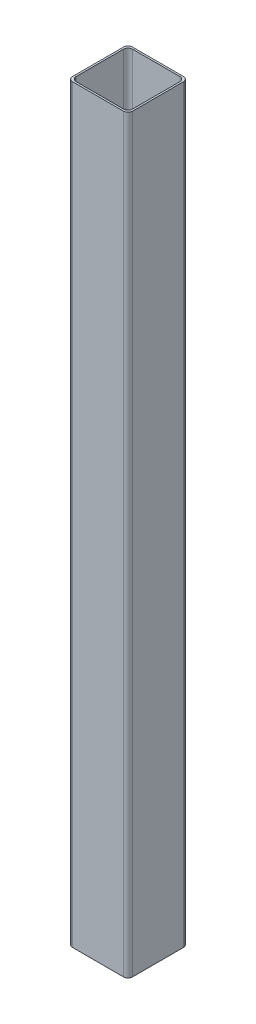
SolidWorks part; units mm, degrees
ref_plane "Plano frontal" through (0, 0, 0) normal (0, 0, 1) x (1, 0, 0)
ref_plane "Plano superior" through (0, 0, 0) normal (0, 1, 0) x (1, 0, 0)
ref_plane "Plano direito" through (0, 0, 0) normal (1, 0, 0) x (0, 0, -1)
sketch "Esboço1" plane through (0, 0, 0) normal (0, 1, 0) x (1, 0, 0)
  line L0 (-18.8, -18.8) -> (-18.8, 18.8)
  line L1 (20, -20) -> (-20, -20)
  line L2 (20, -20) -> (20, 20)
  line L3 (20, 20) -> (-20, 20)
  line L4 (-20, -20) -> (-20, 20)
  line L5 (20, -20) -> (-20, 20) construction
  line L6 (20, 20) -> (-20, -20) construction
  line L7 (18.8, 18.8) -> (-18.8, 18.8)
  line L8 (18.8, -18.8) -> (18.8, 18.8)
  line L9 (18.8, -18.8) -> (-18.8, -18.8)
  point P0 (0, 0)
  dimension "D1" = 40
  dimension "D2" = 40
  dimension "D3" = 1.2
extrude "Ressalto-extrusão1" add sketch "Esboço1" along normal mid plane 500
fillet "Filete1" radius 3 8 edges at (-20, 0, -20) (20, 0, -20) (18.8, 0, -18.8) (18.8, 0, 18.8) (-18.8, 0, 18.8) (-18.8, 0, -18.8) (-20, 0, 20) (20, 0, 20)
